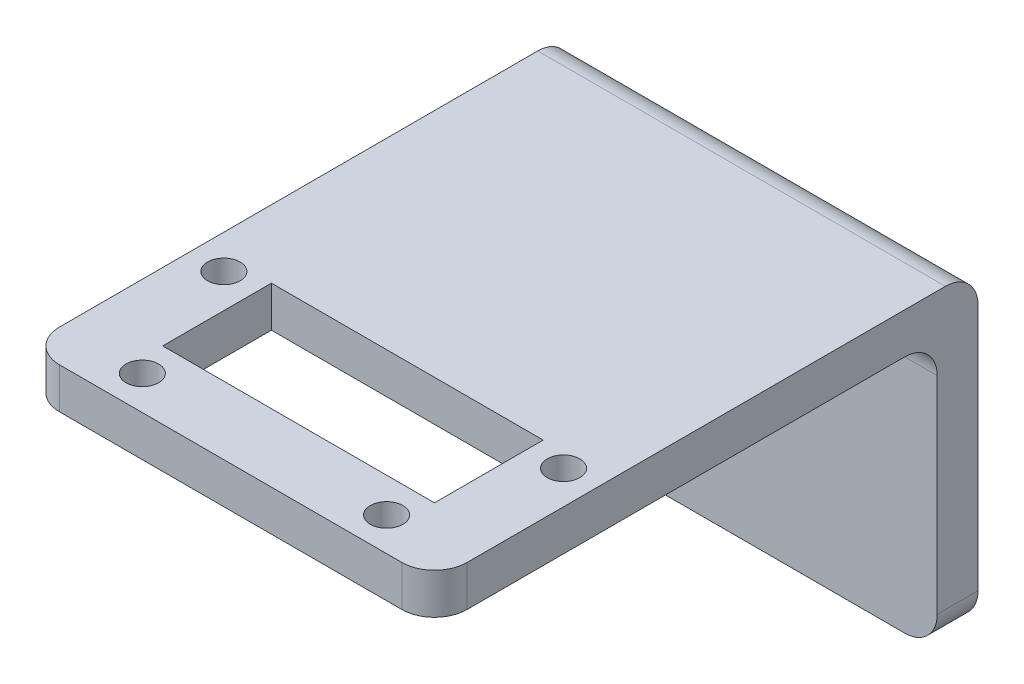
SolidWorks part; units mm, degrees
ref_plane "Plano frontal" through (0, 0, 0) normal (0, 0, 1) x (1, 0, 0)
ref_plane "Plano superior" through (0, 0, 0) normal (0, 1, 0) x (1, 0, 0)
ref_plane "Plano direito" through (0, 0, 0) normal (1, 0, 0) x (0, 0, -1)
sketch "Esboço1" plane through (0, 0, 0) normal (0, 1, 0) x (1, 0, 0)
  line L0 (0, 0) -> (0, 20) construction
  line L1 (-15, 20) -> (15, 20)
  line L2 (0, 0) -> (15, 0) construction
  line L3 (15, -20) -> (15, 20)
  line L4 (-15, 20) -> (-15, -20)
  line L5 (-15, -20) -> (15, -20)
  point P5 (0, 20)
  point P10 (15, 0)
  dimension "D1" = 30
  dimension "D2" = 40
extrude "Ressalto-extrusão1" add sketch "Esboço1" along normal blind 3
sketch "Esboço2" plane through (0, 3, 0) normal (0, 1, 0) x (1, 0, 0)
  line L4 (0, -20) -> (0, 20) construction
  line L5 (-15, -20) -> (15, -20) construction
  line L6 (15, 20) -> (-15, 20) construction
  line L7 (-10, -7) -> (10, -7)
  line L9 (-8.8957, -8) -> (9.1043, -8) construction
  line L10 (10, -7) -> (10, -15)
  line L11 (10, -15) -> (-10, -15)
  line L12 (-10, -15) -> (-10, -7)
  point P3 (0, -7)
  dimension "D1" = 0
  dimension "D2" = 20
  dimension "D3" = 1
  dimension "D4" = 8
extrude "Corte-extrusão1" cut sketch "Esboço2" against normal through all
sketch "Esboço3" plane through (0, 0, 0) normal (0, -1, 0) x (1, 0, 0)
  line L0 (-15, -20) -> (-15, 20) construction
  line L1 (-15, 20) -> (15, 20) construction
  line L3 (0, 20) -> (0.0283, 5) construction
  line L4 (-15.9979, 5) -> (16.0545, 5) construction
  line L5 (54.6527, 5) -> (-54.4441, 5) construction
  circle A0 centre (-9, 17.5) radius 1.2
  circle A2 centre (-12.5, 8) radius 1.2
  circle A4 centre (12.5451, 8.0472) radius 1.2
  circle A5 centre (9.0094, 17.5339) radius 1.2
  dimension "D1" = 2.4
  dimension "D7" = 2.4
  dimension "D2" = 6
  dimension "D3" = 2.5
  dimension "D9" = 2.5
  dimension "D11" = 3
extrude "Corte-extrusão2" cut sketch "Esboço3" against normal through all
sketch "Esboço4" plane through (0, 0, 0) normal (0, -1, 0) x (1, 0, 0)
  line L0 (-15, -17) -> (15, -17)
  line L4 (-15, 20) -> (-15, -20)
  line L5 (-15, -20) -> (15, -20)
  line L6 (15, -20) -> (15, 20)
  line L7 (15, 20) -> (-15, 20)
  line L8 (-15, 20) -> (-15, -20)
  line L9 (-15, -20) -> (15, -20)
  line L10 (15, -20) -> (15, 20)
  line L11 (15, 20) -> (-15, 20)
  dimension "D2" = 3
  dimension "D1" = 0
extrude "Ressalto-extrusão2" add sketch "Esboço4" along normal blind 20
fillet "Filete5" radius 2.4 1 edges at (0, 0, -17)
fillet "Filete6" radius 2.4 1 edges at (0, 3, -20)
fillet "Filete7" radius 2.4 2 edges at (15, 1.5, 20) (-15, 1.5, 20)
fillet "Filete8" radius 2.4 2 edges at (-15, -20, -18.5) (15, -20, -18.5)
